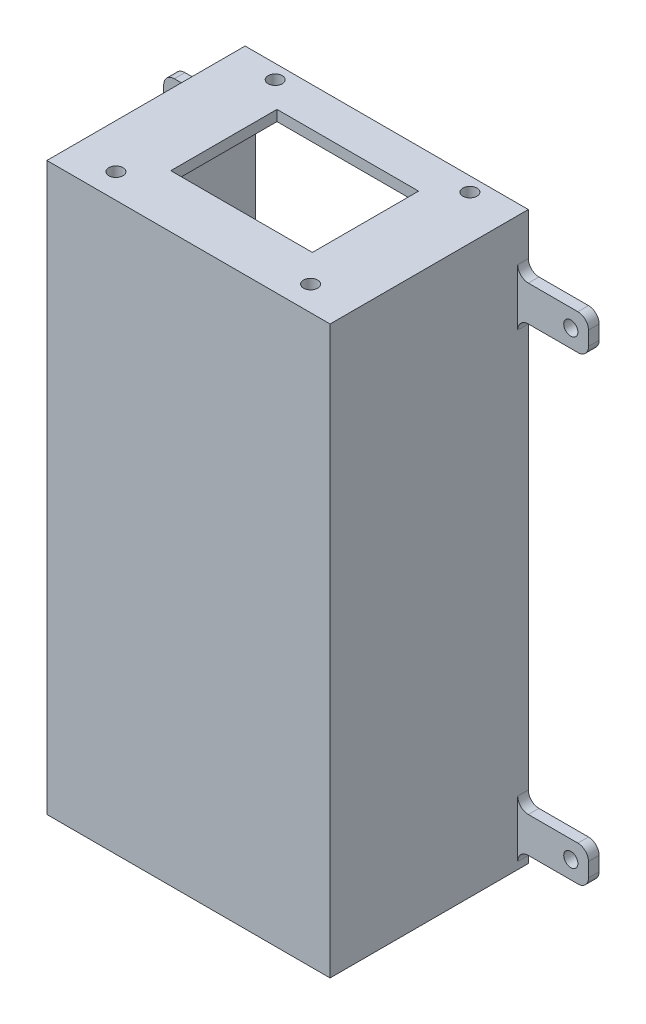
SolidWorks part; units mm, degrees
ref_plane "Front Plane" through (0, 0, 0) normal (0, 0, 1) x (1, 0, 0)
ref_plane "Top Plane" through (0, 0, 0) normal (0, 1, 0) x (1, 0, 0)
ref_plane "Right Plane" through (0, 0, 0) normal (1, 0, 0) x (0, 0, -1)
sketch "Sketch1" plane through (0, 0, 0) normal (0, 0, 1) x (1, 0, 0)
  line L1 (40, -80) -> (-40, -80)
  line L2 (40, -80) -> (40, 80)
  line L3 (40, 80) -> (-40, 80)
  line L4 (-40, -80) -> (-40, 80)
  line L5 (40, -80) -> (-40, 80) construction
  line L6 (40, 80) -> (-40, -80) construction
  point P0 (0, 0)
  dimension "D1" = 160
  dimension "D2" = 80
extrude "Boss-Extrude1" add sketch "Sketch1" along normal blind 56
shell "Shell1" thickness 3
sketch "Sketch2" plane through (0, 80, 0) normal (0, 1, 0) x (1, 0, 0)
  line L0 (40, -56) -> (-40, -56) construction
  line L1 (20, -41) -> (-20, -41)
  line L2 (20, -41) -> (20, -11)
  line L3 (20, -11) -> (-20, -11)
  line L4 (-20, -41) -> (-20, -11)
  line L5 (20, -41) -> (-20, -11) construction
  line L6 (20, -11) -> (-20, -41) construction
  point P0 (0, -26)
  dimension "D1" = 15
  dimension "D2" = 30
  dimension "D3" = 40
extrude "Cut-Extrude1" cut sketch "Sketch2" against normal blind 70
sketch "Sketch4" plane through (0, -80, 0) normal (0, -1, 0) x (-1, 0, 0)
  line L0 (40, 0) -> (-40, 0) construction
  line L1 (-35, -15) -> (35, -15)
  line L2 (-35, -15) -> (-35, 0)
  line L3 (-35, 0) -> (35, 0)
  line L4 (35, -15) -> (35, 0)
  line L5 (-35, -15) -> (35, 0) construction
  line L6 (-35, 0) -> (35, -15) construction
  point P0 (0, -7.5)
  dimension "D1" = 15
  dimension "D2" = 70
extrude "Cut-Extrude3" cut sketch "Sketch4" against normal blind 70
sketch "Sketch5" plane through (0, 0, 0) normal (0, 0, -1) x (-1, 0, 0)
  line L0 (40, 80) -> (40, -80) construction
  line L1 (40, 65) -> (60, 65)
  line L2 (40, 65) -> (40, 55)
  line L3 (40, 55) -> (60, 55)
  line L4 (60, 65) -> (60, 55)
  line L5 (40, 65) -> (60, 55) construction
  line L6 (40, 55) -> (60, 65) construction
  line L7 (-40, 80) -> (40, 80) construction
  line L8 (40, -65) -> (60, -65)
  line L9 (40, -65) -> (40, -75)
  line L10 (40, -75) -> (60, -75)
  line L11 (60, -65) -> (60, -75)
  line L12 (40, -65) -> (60, -75) construction
  line L13 (40, -75) -> (60, -65) construction
  line L14 (40, -80) -> (35, -80) construction
  circle A0 centre (55, 60) radius 2
  circle A1 centre (55, -70) radius 2
  point P4 (50, 60)
  point P11 (50, -70)
  dimension "D1" = 4
  dimension "D4" = 15
  dimension "D6" = 15
  dimension "D2" = 10
  dimension "D3" = 20
  dimension "D5" = 5
extrude "Boss-Extrude2" add sketch "Sketch5" against normal blind 3
mirror "Mirror1" about plane through (0, 0, 0) normal (1, 0, 0) of "Boss-Extrude2"
sketch "Sketch6" plane through (0, 80, 0) normal (0, 1, 0) x (1, 0, 0)
  line L10 (40, -56) -> (-40, -56) construction
  line L18 (-27.5, -49) -> (27.5, -49) construction
  line L19 (-27.5, -4) -> (-27.5, -49) construction
  line L20 (27.5, -4) -> (-27.5, -4) construction
  line L21 (27.5, -49) -> (27.5, -4) construction
  circle A0 centre (-27.5, -4) radius 2
  circle A2 centre (27.5, -4) radius 2
  circle A3 centre (27.5, -49) radius 2
  circle A4 centre (-27.5, -49) radius 2
  point P4 (0, -4)
  dimension "D2" = 4
  dimension "D1" = 55
  dimension "D3" = 45
  dimension "D4" = 7
extrude "Cut-Extrude4" cut sketch "Sketch6" against normal blind 3
fillet "Fillet1" radius 3 18 edges at (35, -78.5, 15) (-35, -78.5, 15) (-40, -75, 1.5) (-60, -75, 1.5) (-60, -65, 1.5) (-40, -65, 1.5) (-40, 55, 1.5) (-60, 55, 1.5) (-60, 65, 1.5) (-40, 65, 1.5) (40, 65, 1.5) (40, 55, 1.5) (60, 65, 1.5) (60, 55, 1.5) (60, -75, 1.5) (60, -65, 1.5) (40, -65, 1.5) (40, -75, 1.5)
